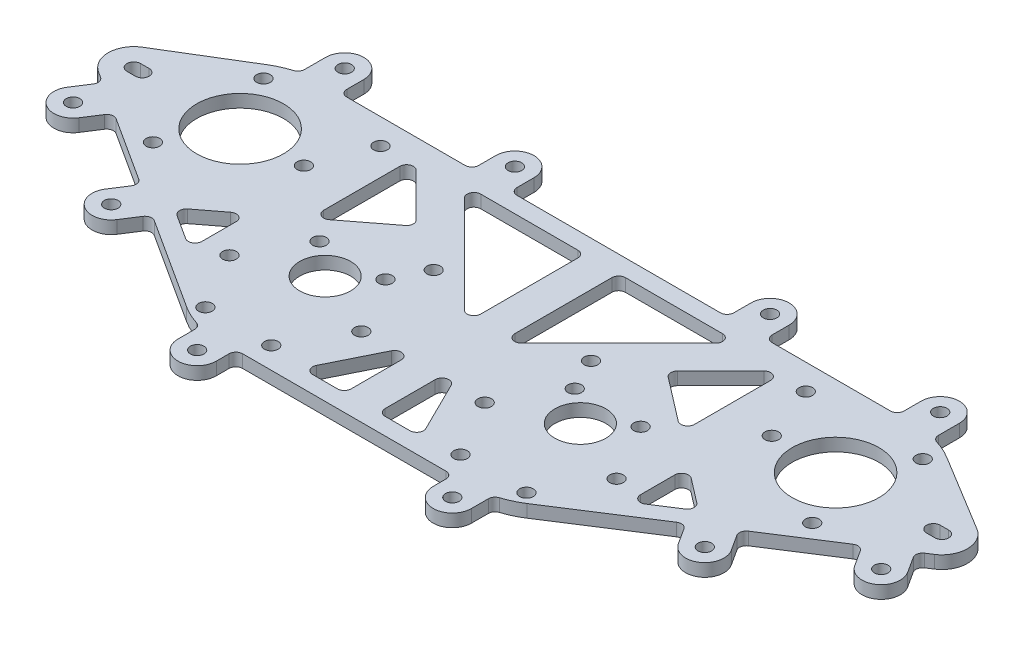
SolidWorks part; units mm, degrees
material "Thornel Mat VMA"
ref_plane "前视基准面" through (0, 0, 0) normal (0, 0, 1) x (1, 0, 0)
ref_plane "上视基准面" through (0, 0, 0) normal (0, 1, 0) x (1, 0, 0)
ref_plane "右视基准面" through (0, 0, 0) normal (1, 0, 0) x (0, 0, -1)
sketch "草图1" plane through (0, 0, 0) normal (0, 1, 0) x (1, 0, 0)
  line L0 (-60, 0) -> (-60, -7) construction
  line L1 (-60, -7) -> (-44.5, -7) construction
  line L2 (0, 0) -> (0, -7) construction
  line L3 (0, -7) -> (-15.5, -7) construction
  line L4 (-60, 0) -> (0, 0) construction
  line L5 (0, -7) -> (-7.75, 6.4234) construction
  line L6 (0, -7) -> (7.75, 6.4234) construction
  line L7 (0, -7) -> (15.5, -7) construction
  line L8 (0, -7) -> (7.75, -20.4234) construction
  line L9 (0, -7) -> (-7.75, -20.4234) construction
  line L10 (-60, -7) -> (-52.25, -20.4234) construction
  line L11 (-60, -7) -> (-67.75, -20.4234) construction
  line L12 (-60, -7) -> (-75.5, -7) construction
  line L13 (-60, -7) -> (-67.75, 6.4234) construction
  line L14 (-60, -7) -> (-52.25, 6.4234) construction
  line L15 (-100, 20) -> (-125, 20) construction
  line L16 (-100, 20) -> (-85, 20) construction
  line L17 (-100, 20) -> (-107.5, 7.0096) construction
  line L18 (-100, 20) -> (-107.5, 32.9904) construction
  line L19 (-125, 21.6) -> (-123, 21.6)
  line L20 (-125, 18.4) -> (-123, 18.4)
  line L21 (-30, 0) -> (-30, 39) construction
  line L22 (-100, 44.6) -> (-60, 44.6) construction
  line L23 (-100, 44.6) -> (-100, 20) construction
  line L24 (-60, 44.6) -> (-60, 0) construction
  line L25 (-60, -7) -> (-60, -30.1) construction
  line L26 (0, 0) -> (0, -7) construction
  line L27 (0, -7) -> (0, -30.1) construction
  line L28 (0, 44.6) -> (0, 0) construction
  line L29 (40, 44.6) -> (40, 20) construction
  line L30 (40, 44.6) -> (0, 44.6) construction
  line L31 (40, 20) -> (47.5, 32.9904) construction
  line L32 (40, 20) -> (47.5, 7.0096) construction
  line L33 (40, 20) -> (25, 20) construction
  line L34 (40, 20) -> (65, 20) construction
  line L35 (65, 18.4) -> (63, 18.4)
  line L36 (65, 21.6) -> (63, 21.6)
  line L37 (-100, 39) -> (40, 39)
  line L38 (-104.5, 44.6) -> (-104.5, 38.4594)
  line L39 (-95.5, 44.6) -> (-95.5, 39)
  line L40 (-64.5, 44.6) -> (-64.5, 39)
  line L41 (-55.5, 44.6) -> (-55.5, 39)
  line L42 (-4.5, 44.6) -> (-4.5, 39)
  line L43 (4.5, 44.6) -> (4.5, 39)
  line L44 (44.5, 44.6) -> (44.5, 38.4594)
  line L45 (35.5, 44.6) -> (35.5, 39)
  line L46 (-109.88, 36.2292) -> (-128.12, 25.125)
  line L47 (-128.2491, 14.9559) -> (-70.0181, -22.5528)
  line L48 (-64.5, -30.1) -> (-64.5, -24.9444)
  line L49 (-60, -25.5) -> (0, -25.5)
  line L50 (4.5, -30.1) -> (4.5, -24.9444)
  line L51 (-4.5, -30.1) -> (-4.5, -25.5)
  line L52 (-55.5, -30.1) -> (-55.5, -25.5)
  line L53 (49.88, 36.2292) -> (68.12, 25.125)
  line L54 (68.2491, 14.9559) -> (10.0181, -22.5528)
  line L55 (-62.2843, 35) -> (-34, 35)
  line L56 (-34, 35) -> (-34, 6.7157)
  line L57 (-34, 6.7157) -> (-62.2843, 35)
  line L58 (-73.598, 35) -> (-73.598, 10)
  line L59 (-73.598, 10) -> (-59.4558, 20.8579)
  line L60 (-59.4558, 20.8579) -> (-73.598, 35)
  line L61 (-81.5625, 3.8851) -> (-91.6508, -3.8604)
  line L62 (-91.6508, -3.8604) -> (-81.5625, -10.3586)
  line L63 (-81.5625, -10.3586) -> (-81.5625, 3.8851)
  line L64 (-73.598, 35) -> (-78.4868, 35) construction
  line L65 (31.6508, -3.8604) -> (21.5625, -10.3586)
  line L66 (21.5625, 3.8851) -> (31.6508, -3.8604)
  line L67 (21.5625, -10.3586) -> (21.5625, 3.8851)
  line L68 (13.598, 10) -> (-0.5442, 20.8579)
  line L69 (13.598, 35) -> (13.598, 10)
  line L70 (-0.5442, 20.8579) -> (13.598, 35)
  line L71 (-26, 35) -> (-26, 6.7157)
  line L72 (2.2843, 35) -> (-26, 35)
  line L73 (-26, 6.7157) -> (2.2843, 35)
  line L74 (-48.5, 14) -> (-11.5, 14)
  line L75 (-125, 20) -> (-125, 5.726) construction
  line L76 (-121.2169, 3.2892) -> (-117.9678, 8.3333)
  line L77 (-125.534, 13.207) -> (-128.7831, 8.1628)
  line L78 (-100.3133, -3.0385) -> (-103.5624, -8.0827)
  line L79 (-92.7471, -7.9122) -> (-95.9962, -12.9563)
  line L80 (-34, -1.2843) -> (-34, -21.5)
  line L81 (-34, -21.5) -> (-44, -21.5)
  line L82 (-44, -21.5) -> (-34, -1.2843)
  line L83 (-26, -21.5) -> (-16, -21.5)
  line L84 (-26, -1.2843) -> (-26, -21.5)
  line L85 (-16, -21.5) -> (-26, -1.2843)
  line L86 (32.7471, -7.9122) -> (35.9962, -12.9563)
  line L87 (40.3133, -3.0385) -> (43.5624, -8.0827)
  line L88 (61.2169, 3.2892) -> (57.9678, 8.3333)
  line L89 (65.534, 13.207) -> (68.7831, 8.1628)
  line L90 (-125, 20) -> (-123, 20) construction
  line L91 (-131, 20) -> (-131, 77.1216) construction
  line L92 (71, 20) -> (71, 77.1216) construction
  circle A0 centre (0, 0) radius 6
  circle A1 centre (-60, 0) radius 6
  circle A2 centre (-15.5, -7) radius 1.6
  circle A3 centre (-44.5, -7) radius 1.6
  circle A4 centre (-7.75, 6.4234) radius 1.6
  circle A5 centre (7.75, 6.4234) radius 1.6
  circle A6 centre (15.5, -7) radius 1.6
  circle A7 centre (7.75, -20.4234) radius 1.6
  circle A8 centre (-7.75, -20.4234) radius 1.6
  circle A9 centre (-52.25, -20.4234) radius 1.6
  circle A10 centre (-67.75, -20.4234) radius 1.6
  circle A11 centre (-75.5, -7) radius 1.6
  circle A12 centre (-67.75, 6.4234) radius 1.6
  circle A13 centre (-52.25, 6.4234) radius 1.6
  circle A14 centre (-60, -7) radius 18.5
  circle A15 centre (-100, 20) radius 3
  arc A16 (-125, 21.6) -> (-125, 18.4) centre (-125, 20) ccw
  circle A18 centre (-85, 20) radius 1.6
  circle A19 centre (-107.5, 7.0096) radius 1.6
  circle A20 centre (-107.5, 32.9904) radius 1.6
  circle A21 centre (-100, 20) radius 19
  arc A22 (-123, 18.4) -> (-123, 21.6) centre (-123, 20) ccw
  circle A23 centre (-125, 20) radius 6
  circle A24 centre (-100, 44.6) radius 1.6
  circle A25 centre (-60, 44.6) radius 1.6
  circle A26 centre (-60, -30.1) radius 1.6
  circle A27 centre (0, -30.1) radius 1.6
  circle A28 centre (0, -7) radius 18.5
  circle A29 centre (0, 44.6) radius 1.6
  circle A30 centre (40, 44.6) radius 1.6
  circle A31 centre (65, 20) radius 6
  arc A32 (63, 18.4) -> (63, 21.6) centre (63, 20) cw
  circle A33 centre (40, 20) radius 19
  circle A34 centre (47.5, 32.9904) radius 1.6
  circle A35 centre (47.5, 7.0096) radius 1.6
  circle A36 centre (25, 20) radius 1.6
  arc A37 (65, 21.6) -> (65, 18.4) centre (65, 20) cw
  circle A38 centre (40, 20) radius 3
  circle A39 centre (-100, 44.6) radius 4.5
  circle A40 centre (-60, 44.6) radius 4.5
  circle A41 centre (-60, -30.1) radius 4.5
  circle A42 centre (0, -30.1) radius 4.5
  circle A43 centre (40, 44.6) radius 4.5
  circle A44 centre (0, 44.6) radius 4.5
  circle A45 centre (-80, 33) radius 1.6
  circle A48 centre (-99.7793, -10.5195) radius 1.6
  circle A49 centre (-125, 5.726) radius 1.6
  circle A50 centre (-125, 5.726) radius 4.5
  circle A51 centre (-99.7793, -10.5195) radius 4.5
  circle A52 centre (39.7793, -10.5195) radius 1.6
  circle A53 centre (39.7793, -10.5195) radius 4.5
  circle A54 centre (65, 5.726) radius 1.6
  circle A55 centre (65, 5.726) radius 4.5
  circle A56 centre (20, 33) radius 1.6
  circle A57 centre (-100, 20) radius 10.2
  circle A58 centre (40, 20) radius 10.2
  circle A60 centre (-48.5, 14) radius 1.6
  circle A61 centre (-11.5, 14) radius 1.6
  point P23 (0, -7)
  point P34 (-60, -7)
  point P46 (-100, 20)
  point P162 (-119.5923, 5.8112)
  point P173 (59.5923, 5.8112)
  point P188 (-30, 14)
  dimension "D1" = 12
  dimension "D4" = 3.2
  dimension "D9" = 6
  dimension "D10" = 3.2
  dimension "D12" = 3.2
  dimension "D16" = 37
  dimension "D17" = 38
  dimension "D19" = 12
  dimension "D20" = 3.2
  dimension "D22" = 23.1
  dimension "D23" = 3.2
  dimension "D24" = 9
  dimension "D25" = 4
  dimension "D34" = 20
  dimension "D35" = 3.2
  dimension "D36" = 3.2
  dimension "D42" = 9
  dimension "D40" = 6
  dimension "D39" = 3.2
  dimension "D43" = 9
  dimension "D48" = 20.4
  dimension "D50" = 3.2
  dimension "D2" = 7
  dimension "D3" = 15.5
  dimension "D7" = 60
  dimension "D8" = 15
  dimension "D11" = 25
  dimension "D14" = 40
  dimension "D15" = 20
  dimension "D18" = 2
  dimension "D21" = 24.6
  dimension "D26" = 12
  dimension "D27" = 4
  dimension "D28" = 4
  dimension "D29" = 40
  dimension "D30" = 45
  dimension "D31" = 8
  dimension "D32" = 25
  dimension "D33" = 20
  dimension "D37" = 13
  dimension "D38" = 6
  dimension "D41" = 90
  dimension "D44" = 4
  dimension "D45" = 8
  dimension "D46" = 10
  dimension "D47" = 30
  dimension "D49" = 37
  dimension "D51" = 25
  dimension "D5" = 6
  dimension "D6" = 6
  dimension "D13" = 3
extrude "凸台-拉伸1" add sketch "草图1" along normal blind 3 contours A31 A33 L37 A21 A23 L47 A14 L49 A28 L54 L73 L71 L72 L63 L62 L61 L60 L59 L58 L56 L57 L55 L65 L67 L66 L68 L70 L69 | A28 A0 A2 A4 A5 A6 A7 A8 | A42 A27 | L51 A42 L50 A28 L49 | A41 L52 L49 A14 L48 | A41 A26 | A14 A1 A3 A9 A10 A11 A12 A13 | A21 A15 A18 A19 A20 | A23 A21 L46 | A23 A22 L20 A16 L19 | A39 L38 A21 L37 L39 | A40 L40 L37 L41 | A40 A25 | A39 A24 | L43 A44 L42 L37 | A44 A29 | A43 A30 | L44 A43 L45 L37 A33 | A33 A36 A34 A35 A38 | L53 A33 A31 | A31 L36 A37 L35 A32 | A50 L76 L47 L77 | A50 A49 | A51 A48 | A51 L79 L47 L78 | A53 A52 | L86 A53 L87 L54 | A55 A54 | L88 A55 L89 L54
fillet "圆角1" radius 1.6 44 edges at (-4.5, 1.5, -39) (35.5, 1.5, -39) (44.5, 1.5, -38.4594) (4.5, 1.5, -39) (-55.5, 1.5, -39) (-64.5, 1.5, -39) (-95.5, 1.5, -39) (-104.5, 1.5, -38.4594) (-55.5, 1.5, 25.5) (-64.5, 1.5, 24.9444) (-4.5, 1.5, 25.5) (4.5, 1.5, 24.9444) (21.5625, 1.5, -3.8851) (21.5625, 1.5, 10.3586) (31.6508, 1.5, 3.8604) (13.598, 1.5, -10) (13.598, 1.5, -35) (-0.5442, 1.5, -20.8579) (-26, 1.5, -6.7157) (-26, 1.5, -35) (2.2843, 1.5, -35) (-62.2843, 1.5, -35) (-34, 1.5, -35) (-34, 1.5, -6.7157) (-81.5625, 1.5, 10.3586) (-91.6508, 1.5, 3.8604) (-81.5625, 1.5, -3.8851) (-73.598, 1.5, -10) (-59.4558, 1.5, -20.8579) (-73.598, 1.5, -35) (-34, 1.5, 21.5) (-44, 1.5, 21.5) (-34, 1.5, 1.2843) (-125.534, 1.5, -13.207) (-117.9678, 1.5, -8.3333) (-100.3133, 1.5, 3.0385) (-92.7471, 1.5, 7.9122) (65.534, 1.5, -13.207) (57.9678, 1.5, -8.3333) (32.7471, 1.5, 7.9122) (40.3133, 1.5, 3.0385) (-26, 1.5, 21.5) (-16, 1.5, 21.5) (-26, 1.5, 1.2843)
equation "\"3。2\"=10"
